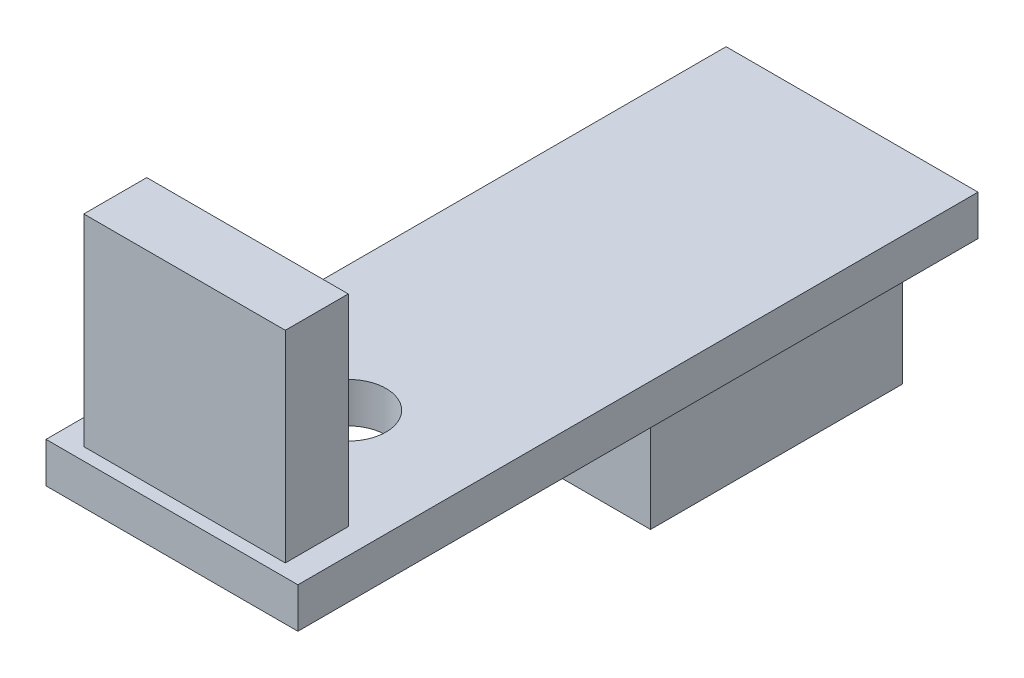
SolidWorks part; units mm, degrees
ref_plane "前视基准面" through (0, 0, 0) normal (0, 0, 1) x (1, 0, 0)
ref_plane "上视基准面" through (0, 0, 0) normal (0, 1, 0) x (1, 0, 0)
ref_plane "右视基准面" through (0, 0, 0) normal (1, 0, 0) x (0, 0, -1)
sketch "草图1" plane through (0, 0, 0) normal (0, 1, 0) x (1, 0, 0)
  line L1 (-5, 20) -> (5, 20)
  line L2 (-5, 20) -> (-5, -7)
  line L3 (-5, -7) -> (5, -7)
  line L4 (5, 20) -> (5, -7)
  circle A0 centre (0, 0) radius 1.5
  point P7 (0, 0)
  point P8 (0, -7)
  dimension "D1" = 3
  dimension "D2" = 7
  dimension "D3" = 10
  dimension "D4" = 27
extrude "凸台-拉伸1" add sketch "草图1" along normal blind 1.6
sketch "草图2" plane through (0, 1.6, 0) normal (0, 1, 0) x (1, 0, 0)
  line L0 (-5, -7) -> (5, -7) construction
  line L1 (-4, -4) -> (4, -4)
  line L2 (-4, -4) -> (-4, -6.5)
  line L3 (-4, -6.5) -> (4, -6.5)
  line L4 (4, -4) -> (4, -6.5)
  point P6 (0, -4)
  point P7 (0, -7)
  dimension "D1" = 3
  dimension "D2" = 0.5
  dimension "D3" = 8
extrude "凸台-拉伸2" add sketch "草图2" along normal blind 8
sketch "草图3" plane through (0, 0, 0) normal (0, -1, 0) x (1, 0, 0)
  line L0 (5, -20) -> (-5, -20) construction
  line L1 (-2.5, -9.5) -> (2.5, -9.5)
  line L2 (-2.5, -9.5) -> (-2.5, -19.5)
  line L3 (-2.5, -19.5) -> (2.5, -19.5)
  line L4 (2.5, -9.5) -> (2.5, -19.5)
  point P6 (0, -9.5)
  dimension "D1" = 5
  dimension "D2" = 10.5
  dimension "D3" = 0.5
extrude "凸台-拉伸3" add sketch "草图3" along normal blind 6
